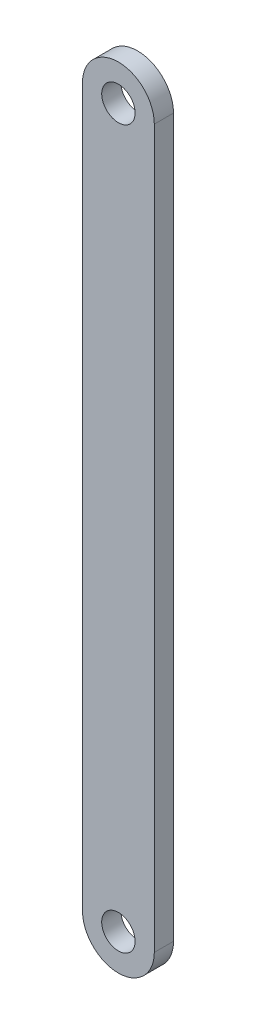
SolidWorks part; units mm, degrees
ref_plane "Front Plane" through (0, 0, 0) normal (0, 0, 1) x (1, 0, 0)
ref_plane "Top Plane" through (0, 0, 0) normal (0, 1, 0) x (1, 0, 0)
ref_plane "Right Plane" through (0, 0, 0) normal (1, 0, 0) x (0, 0, -1)
sketch "Sketch1" plane through (0, 0, 0) normal (0, 0, 1) x (1, 0, 0)
  line L0 (0, 0) -> (0, 186.85) construction
  line L1 (-9.35, 0) -> (-9.35, 186.85)
  line L2 (9.35, 0) -> (9.35, 186.85)
  arc A1 (-9.35, 0) -> (9.35, 0) centre (0, 0) ccw
  arc A2 (9.35, 186.85) -> (-9.35, 186.85) centre (0, 186.85) ccw
  circle A3 centre (0, 0) radius 4.35
  circle A4 centre (0, 186.85) radius 4.35
  point P3 (0, 93.425)
  dimension "D1" = 8.7
  dimension "D2" = 8.7
  dimension "D4" = 5
  dimension "D3" = 186.85
extrude "Boss-Extrude1" add sketch "Sketch1" along normal blind 5
